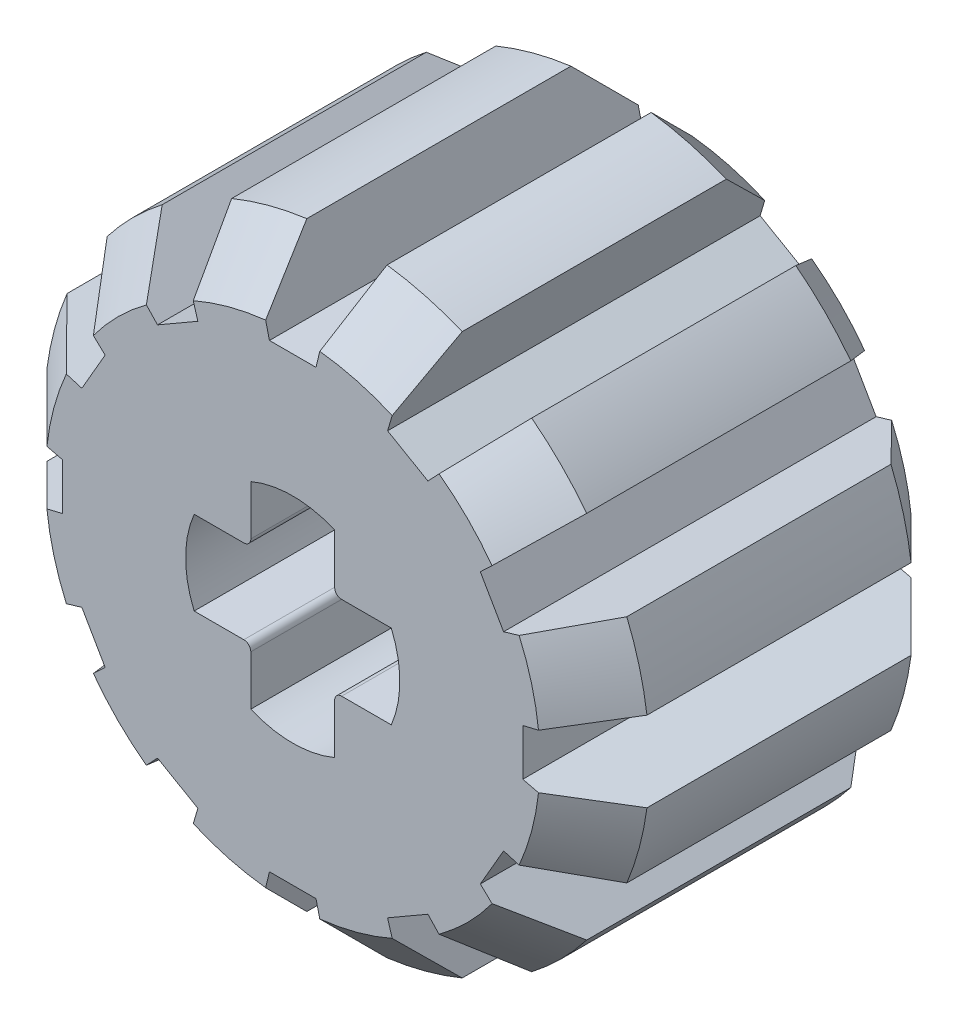
SolidWorks part; units mm, degrees
material "ABS"
ref_plane "Front Plane" through (0, 0, 0) normal (0, 0, 1) x (1, 0, 0)
ref_plane "Top Plane" through (0, 0, 0) normal (0, 1, 0) x (1, 0, 0)
ref_plane "Right Plane" through (0, 0, 0) normal (1, 0, 0) x (0, 0, -1)
sketch "Sketch2" plane through (0, 0, 0) normal (0, 0, 1) x (1, 0, 0)
  line L0 (0, 2.3) -> (0, -2.3) construction
  line L1 (-2.3, 0) -> (2.3, 0) construction
  line L2 (-0.9, 2.1166) -> (-0.9, 1.05)
  line L3 (-2.1166, -0.9) -> (-1.05, -0.9)
  line L4 (0.9, 2.1166) -> (0.9, 1.05)
  line L5 (-2.1166, 0.9) -> (-1.05, 0.9)
  line L6 (-2.3, 0.9) -> (2.3, 0.9) construction
  line L7 (-2.3, -0.9) -> (2.3, -0.9) construction
  line L8 (-0.9, 2.3) -> (-0.9, -2.3) construction
  line L9 (0.9, 2.3) -> (0.9, -2.3) construction
  line L10 (-0.9, -1.05) -> (-0.9, -2.1166)
  line L11 (1.05, 0.9) -> (2.1166, 0.9)
  line L12 (0.9, -1.05) -> (0.9, -2.1166)
  line L13 (1.05, -0.9) -> (2.1166, -0.9)
  arc A0 (-0.9, -2.1166) -> (0.9, -2.1166) centre (0, 0) ccw
  arc A1 (2.1166, -0.9) -> (2.1166, 0.9) centre (0, 0) ccw
  arc A2 (0.9, 2.1166) -> (-0.9, 2.1166) centre (0, 0) ccw
  arc A3 (-2.1166, 0.9) -> (-2.1166, -0.9) centre (0, 0) ccw
  arc A4 (0.9, 1.05) -> (1.05, 0.9) centre (1.05, 1.05) ccw
  arc A5 (1.05, -0.9) -> (0.9, -1.05) centre (1.05, -1.05) ccw
  arc A6 (-0.9, -1.05) -> (-1.05, -0.9) centre (-1.05, -1.05) ccw
  arc A7 (-1.05, 0.9) -> (-0.9, 1.05) centre (-1.05, 1.05) ccw
  circle A8 centre (0, 0) radius 6.5
  point P30 (0.9, -0.9)
  dimension "D1" = 4.6
  dimension "D4" = 0.15
  dimension "D5" = 13
  dimension "D2" = 0.9
  dimension "D3" = 0.9
extrude "Boss-Extrude1" add sketch "Sketch2" along normal blind 8
sketch "Sketch3" plane through (0, 0, 8) normal (0, 0, 1) x (1, 0, 0)
  line L0 (-0.875, 6.5) -> (-0.5, 4.94)
  line L2 (0.5, 4.94) -> (0.875, 6.5)
  line L3 (0.875, 6.5) -> (-0.875, 6.5)
  line L4 (0, 6.5) -> (0, -6.5) construction
  line L5 (-0.5, 4.94) -> (0, 4.94)
  line L6 (0, 4.94) -> (0.5, 4.94)
  circle A0 centre (0, 0) radius 6.5 construction
  dimension "D1" = 1
  dimension "D2" = 1.75
  dimension "D3" = 1.56
extrude "Cut-Extrude1" cut sketch "Sketch3" against normal through all
pattern_circular "CirPattern1" count 12 over 360 about axis through (0, 0, 0) along (0, 0, 1) of "Cut-Extrude1"
sketch "Sketch4" plane through (0, 0, 0) normal (0, 1, 0) x (1, 0, 0)
  line L0 (0, 4.6637) -> (0, -12.7831) construction
  line L4 (-6.8127, -8.45) -> (-6.8127, -6.53)
  line L5 (-6.8127, -6.53) -> (-4.85, -8.45)
  line L6 (-4.85, -8.45) -> (-6.8127, -8.45)
  line L7 (8.2316, -4) -> (-7.7746, -4) construction
  line L8 (0.8612, -8) -> (2.4755, -8) construction
  line L10 (-4.85, 0.45) -> (-6.8127, 0.45)
  line L11 (-6.8127, -1.47) -> (-4.85, 0.45)
  line L12 (-6.8127, 0.45) -> (-6.8127, -1.47)
  line L13 (-6.4427, -8) -> (-6.4427, 0) construction
  line L14 (-4.5282, -8) -> (-6.0101, -8) construction
  dimension "D1" = 4
  dimension "D2" = 2.53
  dimension "D3" = 0.45
  dimension "D4" = 4.85
  dimension "D5" = 0.37
revolve "Cut-Revolve1" cut sketch "Sketch4" angle 360 about L0
